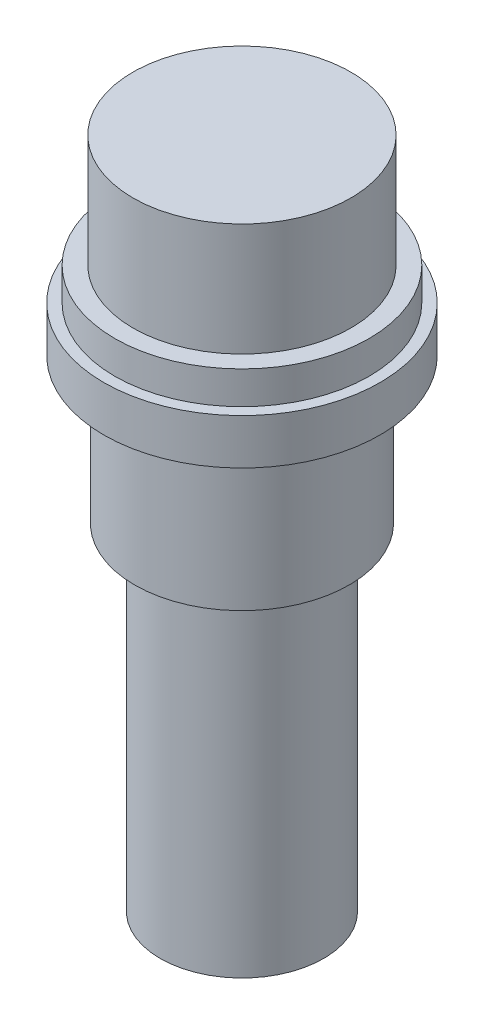
SolidWorks part; units mm, degrees
ref_plane "前视基准面" through (0, 0, 0) normal (0, 0, 1) x (1, 0, 0)
ref_plane "上视基准面" through (0, 0, 0) normal (0, 1, 0) x (1, 0, 0)
ref_plane "右视基准面" through (0, 0, 0) normal (1, 0, 0) x (0, 0, -1)
sketch "草图1" plane through (0, 0, 0) normal (0, 0, 1) x (1, 0, 0)
  line L0 (0, 77.7218) -> (0, -62.1775) construction
  line L1 (0, 30.9387) -> (6, 30.9387)
  line L2 (6, 30.9387) -> (6, 24.7387)
  line L3 (6, 24.7387) -> (7, 24.7387)
  line L4 (7, 24.7387) -> (7, 22.9387)
  line L5 (7, 22.9387) -> (7.6, 22.9387)
  line L6 (7.6, 22.9387) -> (7.6, 20.4387)
  line L7 (7.6, 20.4387) -> (5.9, 20.4387)
  line L8 (5.9, 20.4387) -> (5.9, 12.4387)
  line L9 (5.9, 12.4387) -> (4.5, 12.4387)
  line L10 (4.5, 12.4387) -> (4.5, -6.0613)
  line L11 (4.5, -6.0613) -> (0, -6.0613)
  line L12 (0, -6.0613) -> (0, 30.9387)
  dimension "D1" = 37
  dimension "D2" = 6
  dimension "D3" = 6.2
  dimension "D4" = 1.8
  dimension "D5" = 7
  dimension "D6" = 7.6
  dimension "D7" = 2.5
  dimension "D8" = 5.9
  dimension "D9" = 8
  dimension "D10" = 4.5
revolve "旋转1" add sketch "草图1" angle 360 about L0
sketch "草图2" plane through (0, 30.9387, 0) normal (0, 1, 0) x (-1, 0, 0)
  line L0 (-10.1635, 0) -> (8.9571, 0) construction
  line L1 (0, 18.7104) -> (0, -11.5419) construction
ref_plane "基准面1" through (0, 0, 0) normal (-1, 0, 0) x (0, 0, 1)
ref_plane "基准面2" through (0, 0, 0) normal (0, 0, 1) x (1, 0, 0)
sketch "草图3" plane through (0, 30.9387, 0) normal (0, 1, 0) x (-1, 0, 0)
  line L0 (11.4801, 0) -> (-9.388, 0) construction
  line L1 (0, -8.4448) -> (0, 8.3485) construction
